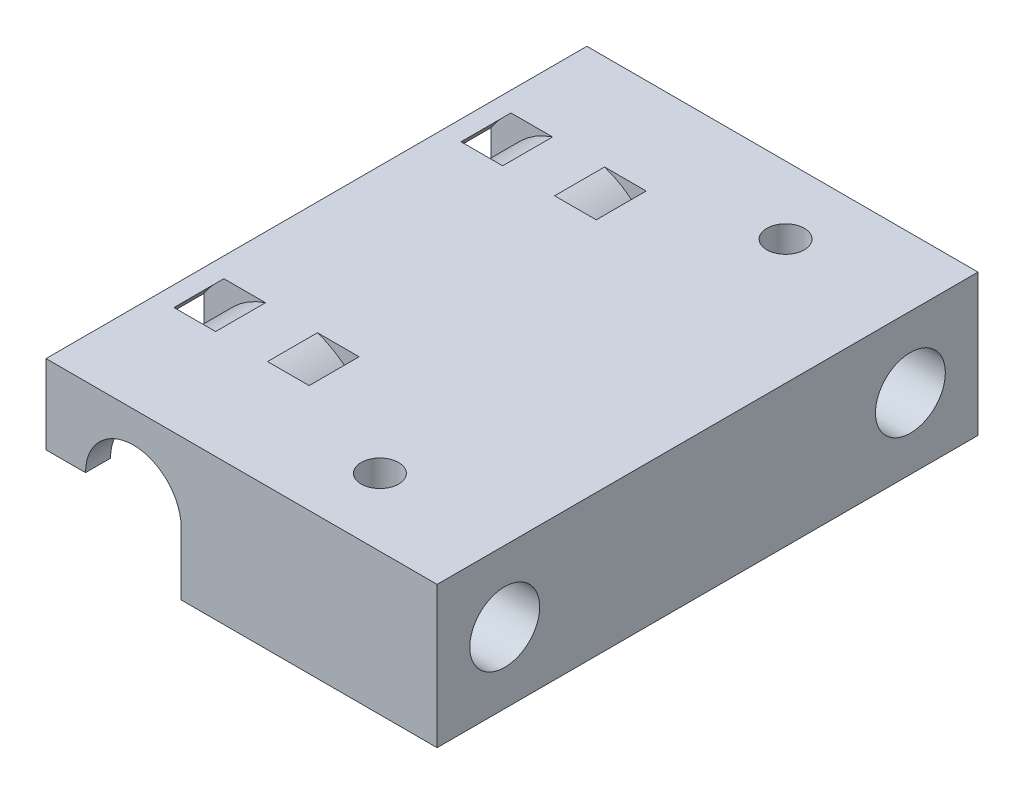
SolidWorks part; units mm, degrees
ref_plane "Спереди" through (0, 0, 0) normal (0, 0, 1) x (1, 0, 0)
ref_plane "Сверху" through (0, 0, 0) normal (0, 1, 0) x (1, 0, 0)
ref_plane "Справа" through (0, 0, 0) normal (1, 0, 0) x (0, 0, -1)
sketch "Эскиз1" plane through (0, 0, 0) normal (0, 1, 0) x (1, 0, 0)
  line L1 (-40.737, 0) -> (6.263, 0)
  line L2 (-40.737, 0) -> (-40.737, 65)
  line L3 (-40.737, 65) -> (6.263, 65)
  line L4 (6.263, 0) -> (6.263, 65)
  dimension "D1" = 65
  dimension "D2" = 47
extrude "Бобышка-Вытянуть1" add sketch "Эскиз1" along normal blind 17
ref_plane "Плоскость1" through (0, 0, -3) normal (0, 0, 1) x (1, 0, 0)
sketch "Эскиз2" plane through (0, 0, -3) normal (0, 0, 1) x (1, 0, 0)
  line L0 (-40.737, -2.3364) -> (-37.737, -2.3364) construction
  line L1 (-37.737, -2.3364) -> (-30.237, -2.3364) construction
  line L2 (-30.237, 0) -> (-30.237, 7.5) construction
  line L3 (-40.737, 0) -> (6.263, 0) construction
  line L4 (-22.487, 7.5) -> (-22.487, 0)
  line L5 (-37.987, 7.5) -> (-40.737, 7.5)
  line L6 (-40.737, 17) -> (-40.737, 0) construction
  line L7 (-40.737, 7.5) -> (-40.737, 0)
  line L8 (-40.737, 0) -> (-22.487, 0)
  arc A0 (-22.487, 7.5) -> (-37.987, 7.5) centre (-30.237, 7.5) ccw
  dimension "D3" = 7.5
  dimension "D4" = 15.5
  dimension "D1" = 3
  dimension "D2" = 7.5
extrude "Вырез-Вытянуть1" cut sketch "Эскиз2" against normal blind 59
sketch "Эскиз5" plane through (0, 0, 0) normal (0, 0, 1) x (1, 0, 0)
  line L0 (-40.737, -2.264) -> (-37.737, -2.264) construction
  line L1 (-37.737, -2.264) -> (-30.237, -2.264) construction
  line L3 (-40.737, 0) -> (6.263, 0) construction
  line L4 (-35.987, 7.5) -> (-40.737, 7.5)
  line L5 (-40.737, 17) -> (-40.737, 0) construction
  line L6 (-40.737, 7.5) -> (-40.737, 0)
  line L7 (-40.737, 0) -> (-24.487, 0)
  line L8 (-24.487, 0) -> (-24.487, 7.5)
  arc A0 (-24.487, 7.5) -> (-35.987, 7.5) centre (-30.237, 7.5) ccw
  dimension "D4" = 11.5
  dimension "D1" = 3
  dimension "D2" = 7.5
extrude "Вырез-Вытянуть2" cut sketch "Эскиз5" against normal through all
ref_plane "Плоскость2" through (0, 0, -27.5) normal (0, 0, 1) x (1, 0, 0)
sketch "Эскиз6" plane through (0, 0, -27.5) normal (0, 0, 1) x (1, 0, 0)
  line L0 (-35.987, 7.5) -> (-40.737, 7.5)
  line L1 (-40.737, 7.5) -> (-40.737, 17)
  line L2 (-40.737, 17) -> (-24.487, 17)
  line L3 (-40.737, 17) -> (6.263, 17) construction
  line L5 (-24.487, 7.5) -> (-24.487, 0)
  line L6 (-24.487, 0) -> (-22.487, 0)
  line L7 (-22.487, 0) -> (-22.487, 17)
  line L8 (-22.487, 17) -> (-24.487, 17)
  arc A0 (-24.487, 7.5) -> (-35.987, 7.5) centre (-30.237, 7.5) ccw
extrude "Бобышка-Вытянуть2" add sketch "Эскиз6" against normal blind 10 contours L7 L8 L2 L1 L0 A0 L5 L6
sketch "Эскиз7" plane through (6.263, 0, 0) normal (1, 0, 0) x (0, 0, -1)
  line L0 (0, 23.207) -> (32.5, 23.207) construction
  line L1 (32.5, 23.207) -> (65, 23.207) construction
  line L2 (0, 25.5825) -> (16.25, 25.5825) construction
  line L3 (0, 29.3553) -> (8.125, 29.3553) construction
  line L4 (65, 25.5825) -> (48.75, 25.5825) construction
  circle A0 centre (8.125, 8.5) radius 4.2
  circle A1 centre (56.875, 8.5) radius 4.2
  dimension "D1" = 8.4
  dimension "D2" = 8.4
  dimension "D3" = 48.75
extrude "Вырез-Вытянуть3" cut sketch "Эскиз7" against normal blind 10
sketch "Эскиз8" plane through (0, 17, 0) normal (0, 1, 0) x (1, 0, 0)
  line L0 (6.263, -4.3445) -> (-3.737, -4.3445) construction
  line L1 (-3.737, -4.3445) -> (-8.737, -4.3445) construction
  line L2 (12.5689, 0) -> (12.5689, 8.125) construction
  line L3 (10.5433, 65) -> (10.5433, 56.875) construction
  circle A0 centre (-8.737, 8.125) radius 2.25
  circle A1 centre (-8.737, 56.875) radius 2.25
  dimension "D4" = 4.5
  dimension "D6" = 4.5
  dimension "D1" = 10
  dimension "D2" = 5
  dimension "D3" = 8.125
  dimension "D5" = 8.125
extrude "Вырез-Вытянуть4" cut sketch "Эскиз8" against normal through all contours A0 | A1
sketch "Эскиз9" plane through (0, 0, 0) normal (0, -1, 0) x (1, 0, 0)
  line L1 (-4.4069, -56.875) -> (-6.5719, -53.125)
  line L2 (-6.5719, -53.125) -> (-10.9021, -53.125)
  line L3 (-10.9021, -53.125) -> (-13.0671, -56.875)
  line L4 (-13.0671, -56.875) -> (-10.9021, -60.625)
  line L5 (-10.9021, -60.625) -> (-6.5719, -60.625)
  line L6 (-6.5719, -60.625) -> (-4.4069, -56.875)
  line L7 (-4.4069, -8.125) -> (-6.5719, -4.375)
  line L8 (-6.5719, -4.375) -> (-10.9021, -4.375)
  line L9 (-10.9021, -4.375) -> (-13.0671, -8.125)
  line L10 (-13.0671, -8.125) -> (-10.9021, -11.875)
  line L11 (-10.9021, -11.875) -> (-6.5719, -11.875)
  line L12 (-6.5719, -11.875) -> (-4.4069, -8.125)
  circle A0 centre (-8.737, -56.875) radius 3.75 construction
  circle A1 centre (-8.737, -8.125) radius 3.75 construction
extrude "Вырез-Вытянуть5" cut sketch "Эскиз9" against normal blind 10
sketch "Эскиз10" plane through (0, 0, -3) normal (0, 0, 1) x (1, 0, 0)
  circle A0 centre (-30.237, 7.5) radius 10
  circle A1 centre (-30.237, 7.5) radius 12.5
  dimension "D1" = 12.5
extrude "Вырез-Вытянуть6" cut sketch "Эскиз10" against normal blind 6 from offset 10 offset against normal yes
sketch "Эскиз11" plane through (0, 0, -27.5) normal (0, 0, 1) x (1, 0, 0)
  circle A0 centre (-30.237, 7.5) radius 10
  circle A1 centre (-30.237, 7.5) radius 12.5
  dimension "D1" = 20
  dimension "D2" = 25
extrude "Вырез-Вытянуть7" cut sketch "Эскиз11" against normal blind 6 from offset 20 offset against normal yes
sketch "Эскиз12" plane through (0, 0, 0) normal (0, 1, 0) x (1, 0, 0)
  line L0 (-53.1902, 0) -> (-53.1902, 65) construction
  line L1 (-53.1902, 65) -> (-53.1902, 62) construction
  line L2 (-53.1902, 62) -> (-53.1902, 37.5) construction
  line L3 (-53.1902, 37.5) -> (-53.1902, 27.5) construction
  line L4 (-9.35, 27.5) -> (9.35, 27.5) construction
  line L5 (-53.1902, 27.5) -> (-53.1902, 3) construction
  line L6 (-9.35, 3) -> (9.35, 3) construction
  line L7 (-53.1902, 3) -> (-53.1902, 0) construction
  dimension "D1" = 24.5
  dimension "D2" = 24.5
